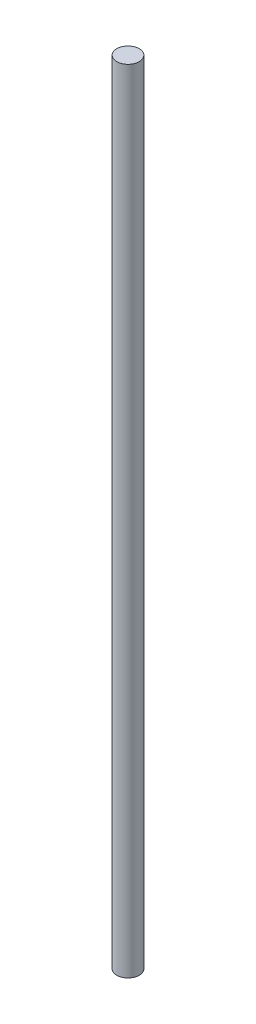
SolidWorks part; units mm, degrees
ref_plane "Alzado" through (0, 0, 0) normal (0, 0, 1) x (1, 0, 0)
ref_plane "Planta" through (0, 0, 0) normal (0, 1, 0) x (1, 0, 0)
ref_plane "Vista lateral" through (0, 0, 0) normal (1, 0, 0) x (0, 0, -1)
sketch "Croquis1" plane through (0, 0, 0) normal (0, 1, 0) x (1, 0, 0)
  circle A0 centre (0, 0) radius 6
  dimension "D1" = 12
extrude "Saliente-Extruir1" add sketch "Croquis1" along normal blind 423
